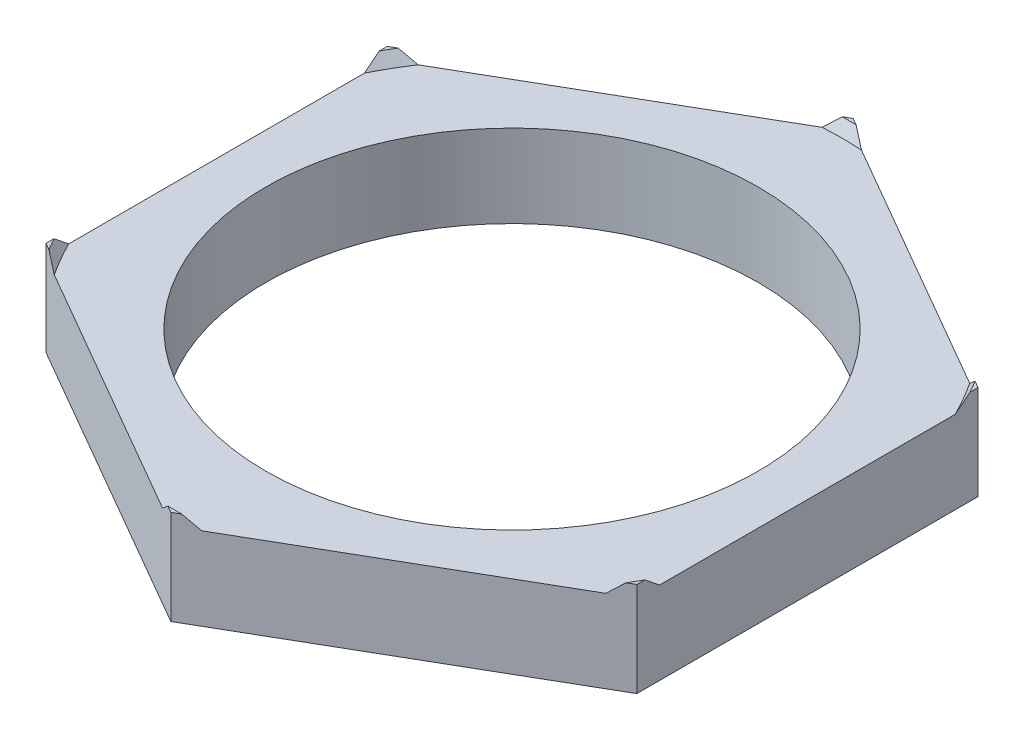
SolidWorks part; units mm, degrees
material "Brass"
ref_plane "Front Plane" through (0, 0, 0) normal (0, 0, 1) x (1, 0, 0)
ref_plane "Top Plane" through (0, 0, 0) normal (0, 1, 0) x (1, 0, 0)
ref_plane "Right Plane" through (0, 0, 0) normal (1, 0, 0) x (0, 0, -1)
sketch "Sketch1" plane through (0, 0, 0) normal (0, 1, 0) x (1, 0, 0)
  line L1 (0, 17.3205) -> (-15, 8.6603)
  line L2 (-15, 8.6603) -> (-15, -8.6603)
  line L3 (-15, -8.6603) -> (0, -17.3205)
  line L4 (0, -17.3205) -> (15, -8.6603)
  line L5 (15, -8.6603) -> (15, 8.6603)
  line L6 (15, 8.6603) -> (0, 17.3205)
  circle A0 centre (0, 0) radius 15 construction
  circle A1 centre (0, 0) radius 12.5
  dimension "D2" = 25
  dimension "D1" = 30
extrude "Extrude1" add sketch "Sketch1" along normal blind 7
sketch "Sketch2" plane through (0, 0, 0) normal (1, 0, 0) x (0, 0, -1)
  line L0 (0, 4.2) -> (-16.7741, 4.2)
  line L1 (-17.3205, 4.8) -> (-17.1205, 4.8)
  line L2 (-17.3205, 4.8) -> (-17.3205, 15.1083)
  line L3 (-17.3205, 15.1083) -> (0, 15.1083)
  line L4 (0, 15.1083) -> (0, 4.2)
  line L5 (-17.3205, 7) -> (-17.3205, 0) construction
  line L6 (-17.1205, 4.8) -> (-16.7741, 4.2)
  dimension "D1" = 0.2
  dimension "D2" = 4.2
  dimension "D3" = 4.8
  dimension "D4" = 60
revolve "Cut-Revolve1" cut sketch "Sketch2" angle 360 about L4
